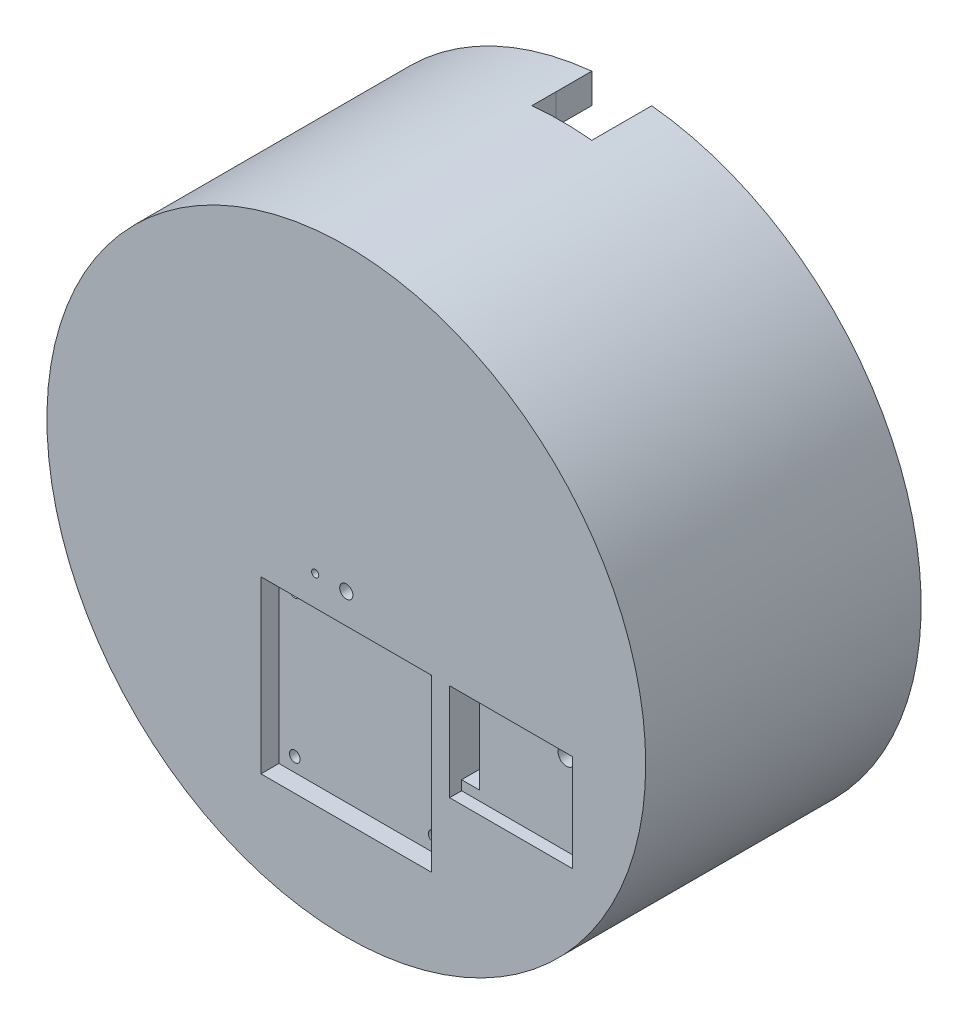
SolidWorks part; units mm, degrees
ref_plane "前视基准面" through (0, 0, 0) normal (0, 0, 1) x (1, 0, 0)
ref_plane "上视基准面" through (0, 0, 0) normal (0, 1, 0) x (1, 0, 0)
ref_plane "右视基准面" through (0, 0, 0) normal (1, 0, 0) x (0, 0, -1)
sketch "草图1" plane through (0, 0, 0) normal (0, 0, 1) x (1, 0, 0)
  circle A0 centre (0, 0) radius 50
  dimension "D1" = 100
extrude "凸台-拉伸1" add sketch "草图1" along normal blind 50
sketch "草图2" plane through (0, 0, 0) normal (0, 0, -1) x (-1, 0, 0)
  circle A0 centre (0, 0) radius 45
  dimension "D1" = 90
extrude "切除-拉伸1" cut sketch "草图2" against normal blind 10
sketch "草图3" plane through (0, 0, 10) normal (0, 0, -1) x (-1, 0, 0)
  circle A0 centre (0, 0) radius 39
  dimension "D1" = 78
extrude "切除-拉伸2" cut sketch "草图3" against normal blind 30
sketch "草图4" plane through (0, 0, 50) normal (0, 0, 1) x (1, 0, 0)
  circle A0 centre (0, 0) radius 1.05
  dimension "D1" = 2.1
extrude "切除-拉伸3" cut sketch "草图4" against normal through all
sketch "草图5" plane through (0, 0, 50) normal (0, 0, 1) x (1, 0, 0)
  line L0 (-5.2, 0) -> (0, 0) construction
  circle A0 centre (-5.2, 0) radius 0.6
  dimension "D1" = 1.2
  dimension "D2" = 5.2
extrude "切除-拉伸4" cut sketch "草图5" against normal through all contours A0
sketch "草图7" plane through (0, 0, 50) normal (0, 0, 1) x (1, 0, 0)
  line L0 (-14.25, -5) -> (14.25, -33.5) construction
  line L1 (-14.25, -5) -> (14.25, -5)
  line L2 (-14.25, -5) -> (-14.25, -33.5)
  line L3 (-14.25, -33.5) -> (14.25, -33.5)
  line L4 (14.25, -5) -> (14.25, -33.5)
  line L5 (14.25, -33.5) -> (14.25, -5) construction
  line L6 (-14.25, -33.5) -> (14.25, -5) construction
  line L7 (0, 0) -> (0, -19.25) construction
  dimension "D1" = 28.5
  dimension "D2" = 28.5
  dimension "D3" = 5
extrude "切除-拉伸5" cut sketch "草图7" against normal blind 3
sketch "草图8" plane through (0, 0, 47) normal (0, 0, 1) x (1, 0, 0)
  line L0 (-11.6, -7.35) -> (11.6, -7.35) construction
  line L1 (11.6, -7.35) -> (11.6, -31.15) construction
  line L2 (11.6, -31.15) -> (-11.6, -31.15) construction
  line L3 (-11.6, -31.15) -> (-11.6, -7.35) construction
  line L5 (11.6, -7.35) -> (-11.6, -31.15) construction
  line L6 (-11.6, -7.35) -> (11.6, -31.15) construction
  line L7 (-14.25, -19.25) -> (14.25, -19.25) construction
  line L8 (-14.25, -5) -> (-14.25, -33.5) construction
  line L9 (14.25, -33.5) -> (14.25, -5) construction
  line L10 (0, -5) -> (0, -33.5) construction
  line L11 (14.25, -5) -> (-14.25, -5) construction
  line L12 (-14.25, -33.5) -> (14.25, -33.5) construction
  line L13 (14.25, -5) -> (-14.25, -5) construction
  line L14 (-9.1, -5) -> (9.1, -5)
  line L15 (-9.1, -5) -> (-9.1, -7.6)
  line L16 (-9.1, -7.6) -> (9.1, -7.6)
  line L17 (9.1, -5) -> (9.1, -7.6)
  circle A0 centre (-11.6, -7.35) radius 0.9
  circle A1 centre (11.6, -7.35) radius 0.9
  circle A2 centre (-11.6, -31.15) radius 0.9
  circle A3 centre (11.6, -31.15) radius 0.9
  point P20 (0, -19.25)
  point P21 (0, -19.25)
  point P28 (0, -7.6)
  dimension "D1" = 1.8
  dimension "D2" = 23.2
  dimension "D3" = 23.8
  dimension "D4" = 2.6
  dimension "D5" = 18.2
extrude "切除-拉伸6" cut sketch "草图8" against normal through all contours L15 L14 L17 L16 | A0 | A1 | A3 | A2
sketch "草图9" plane through (0, 0, 50) normal (0, 0, 1) x (1, 0, 0)
  line L0 (14.25, -5) -> (-14.25, -5) construction
  line L1 (17.25, -5) -> (37.75, -5)
  line L2 (17.25, -5) -> (17.25, -21.2)
  line L3 (17.25, -21.2) -> (37.75, -21.2)
  line L4 (37.75, -5) -> (37.75, -21.2)
  line L5 (14.25, -33.5) -> (14.25, -5) construction
  dimension "D1" = 16.2
  dimension "D2" = 20.5
  dimension "D3" = 3
extrude "切除-拉伸7" cut sketch "草图9" against normal blind 2
sketch "草图10" plane through (0, 0, 48) normal (0, 0, 1) x (1, 0, 0)
  line L0 (17.25, -5) -> (17.25, -21.2) construction
  line L1 (17.25, -6.6) -> (20.25, -6.6)
  line L2 (17.25, -6.6) -> (17.25, -19.6)
  line L3 (17.25, -19.6) -> (20.25, -19.6)
  line L4 (20.25, -6.6) -> (20.25, -19.6)
  line L5 (37.75, -13.1) -> (17.25, -13.1) construction
  line L6 (37.75, -21.2) -> (37.75, -5) construction
  line L7 (37.75, -5) -> (17.25, -5) construction
  circle A0 centre (34.75, -7.5) radius 1.4
  point P12 (17.25, -13.1)
  dimension "D3" = 2.8
  dimension "D1" = 3
  dimension "D2" = 13
  dimension "D4" = 17.5
  dimension "D5" = 2.5
extrude "切除-拉伸8" cut sketch "草图10" against normal through all
sketch "草图11" plane through (0, 0, 50) normal (0, 0, 1) x (1, 0, 0)
  circle A0 centre (0, 0) radius 1.1
  dimension "D1" = 2.2
extrude "切除-拉伸9" cut sketch "草图11" against normal through all
sketch "草图12" plane through (0, 0, 10) normal (0, 0, -1) x (-1, 0, 0)
  line L0 (-42, 0) -> (42, 0) construction
  line L1 (0, 0) -> (0, -42) construction
  circle A0 centre (42, 0) radius 1.45
  circle A1 centre (-42, 0) radius 1.45
  circle A2 centre (0, -42) radius 1.45
  dimension "D1" = 2.9
  dimension "D2" = 42
  dimension "D3" = 42
  dimension "D4" = 42
extrude "切除-拉伸11" cut sketch "草图12" against normal blind 5
sketch "草图13" plane through (0, 0, 0) normal (0, 0, -1) x (-1, 0, 0)
  line L0 (0, 54.7214) -> (0, 44.7214) construction
  line L1 (5, 44.7214) -> (-5, 44.7214)
  line L2 (5, 44.7214) -> (5, 54.7214)
  line L3 (5, 54.7214) -> (-5, 54.7214)
  line L4 (-5, 44.7214) -> (-5, 54.7214)
  circle A0 centre (0, 0) radius 45 construction
  circle A1 centre (0, 0) radius 45 construction
  dimension "D1" = 10
  dimension "D2" = 10
extrude "切除-拉伸12" cut sketch "草图13" against normal up to surface (10 mm away) up to face at (-43.45, 0, 10)
sketch "草图14" plane through (0, 0, 10) normal (0, 0, -1) x (-1, 0, 0)
  line L1 (-5, 51.5025) -> (5.013, 51.5025)
  line L2 (-5, 51.5025) -> (-5, 36.0008)
  line L3 (-5, 36.0008) -> (5.013, 36.0008)
  line L4 (5.013, 51.5025) -> (5.013, 36.0008)
extrude "切除-拉伸14" cut sketch "草图14" against normal blind 4
sketch "草图15" plane through (0, 0, 0) normal (0, 0, -1) x (-1, 0, 0)
  circle A0 centre (0, 0) radius 45.05
  dimension "D1" = 90.1
extrude "切除-拉伸15" cut sketch "草图15" against normal blind 10
sketch "草图16" plane through (5, 0, 0) normal (-1, 0, 0) x (0, 0, 1)
  line L1 (0, 49.7494) -> (4, 49.7494)
  line L2 (0, 49.7494) -> (0, -55.54)
  line L3 (0, -55.54) -> (4, -55.54)
  line L4 (4, 49.7494) -> (4, -55.54)
  dimension "D1" = 4
extrude "切除-拉伸16" cut sketch "草图16" against normal through all both and the other way through all
sketch "草图17" plane through (0, 0, 14) normal (0, 0, -1) x (-1, 0, 0)
  line L0 (-5, 47.0165) -> (5, 47.0165) construction
  line L1 (-5, 49.7494) -> (-5, 38.6782) construction
  line L2 (5, 44.7717) -> (5, 49.7494) construction
